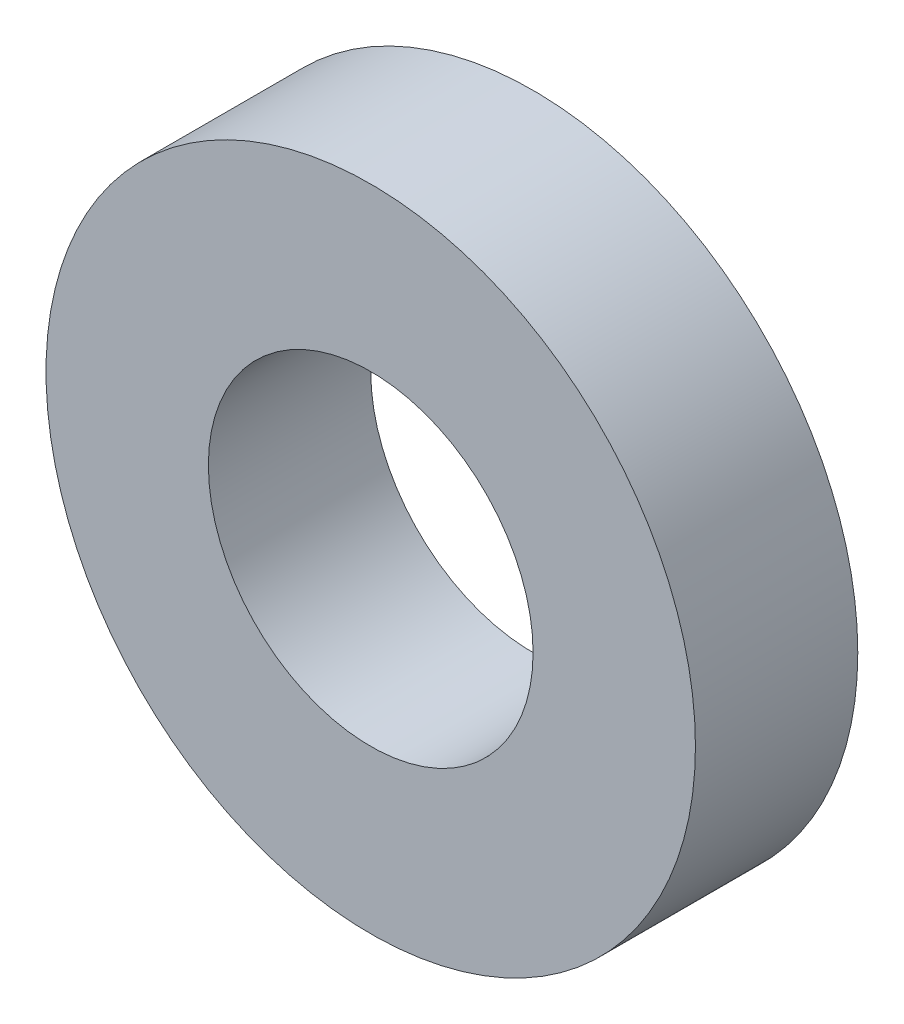
SolidWorks part; units mm, degrees
ref_plane "Front Plane" through (0, 0, 0) normal (0, 0, 1) x (1, 0, 0)
ref_plane "Top Plane" through (0, 0, 0) normal (0, 1, 0) x (1, 0, 0)
ref_plane "Right Plane" through (0, 0, 0) normal (1, 0, 0) x (0, 0, -1)
sketch "Sketch1" plane through (0, 0, 0) normal (0, 0, 1) x (1, 0, 0)
  circle A0 centre (0, 0) radius 6.35
  dimension "D1" = 12.7
extrude "Boss-Extrude1" add sketch "Sketch1" along normal blind 3.175
sketch "Sketch2" plane through (0, 0, 3.175) normal (0, 0, 1) x (1, 0, 0)
  circle A0 centre (0, 0) radius 3.175
  dimension "D1" = 6.35
extrude "Cut-Extrude1" cut sketch "Sketch2" against normal blind 3.175
